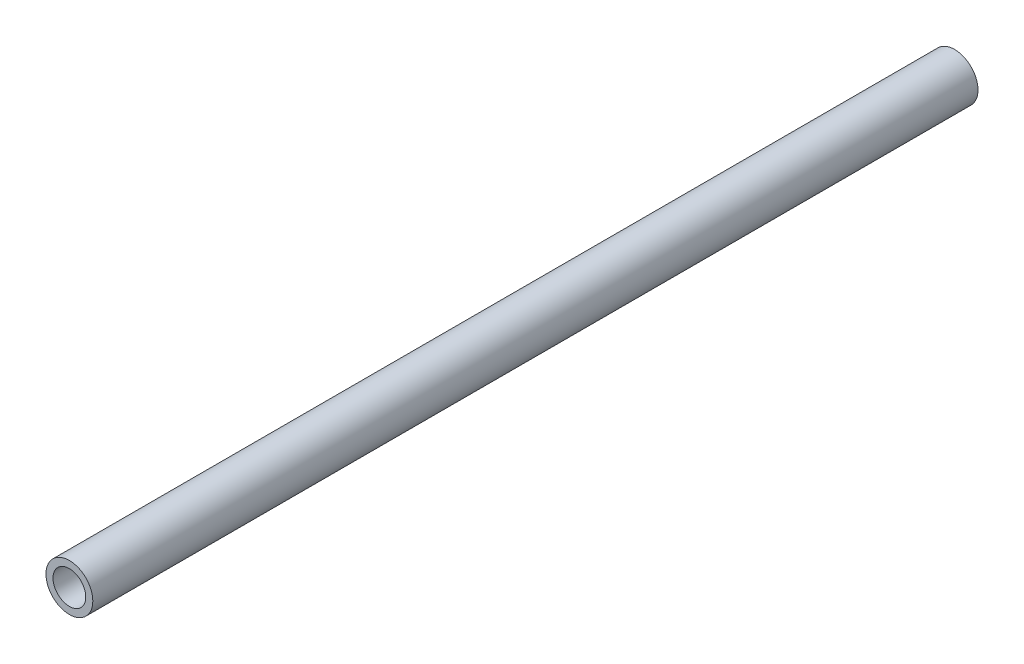
SolidWorks part; units mm, degrees
ref_plane "Front Plane" through (0, 0, 0) normal (1, 0, 0) x (0, 1, 0)
ref_plane "Top Plane" through (0, 0, 0) normal (0, 0, 1) x (0, 1, 0)
ref_plane "Right Plane" through (0, 0, 0) normal (0, 1, 0) x (-1, 0, 0)
sketch "Sketch1" plane through (0, 0, 0) normal (0, 0, 1) x (0, 1, 0)
  circle A0 centre (0, 0) radius 15.875
  circle A1 centre (0, 0) radius 11.1
  dimension "D1" = 31.75
  dimension "D2" = 22.2
extrude "Boss-Extrude1" add sketch "Sketch1" along normal blind 600
equation "\"OD\"= 1.25in"
equation "\"ID\"= 22.2"
equation "\"D1@Sketch1\"=\"OD\""
equation "\"D2@Sketch1\"=\"ID\""
equation "\"L\" = 600"
equation "\"D1@Boss-Extrude1\"=\"L\""
